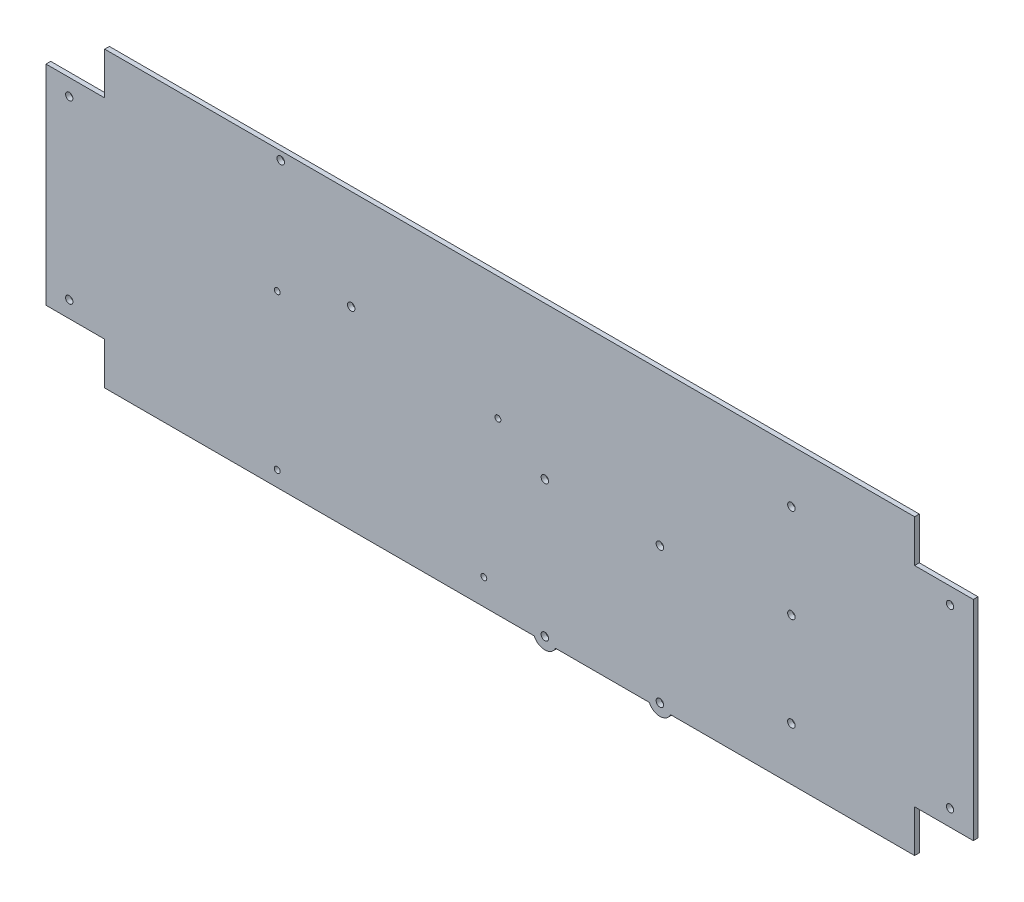
SolidWorks part; units mm, degrees
material "2014 Alloy"
ref_plane "Plan de face" through (0, 0, 0) normal (0, 0, 1) x (1, 0, 0)
ref_plane "Plan de dessus" through (0, 0, 0) normal (0, 1, 0) x (1, 0, 0)
ref_plane "Plan de droite" through (0, 0, 0) normal (1, 0, 0) x (0, 0, -1)
sketch "Sketch1" plane through (0, 0, 0) normal (0, 0, 1) x (1, 0, 0)
  line L1 (-197.5, 62.5) -> (197.5, 62.5)
  line L2 (-197.5, 62.5) -> (-197.5, -62.5)
  line L3 (-197.5, -62.5) -> (197.5, -62.5)
  line L4 (197.5, 62.5) -> (197.5, -62.5)
  line L5 (-197.5, 62.5) -> (197.5, -62.5) construction
  line L6 (-197.5, -62.5) -> (197.5, 62.5) construction
  point P0 (0, 0)
  dimension "D1" = 125
  dimension "D2" = 395
extrude "Boss-Extrude1" add sketch "Sketch1" along normal blind 2
sketch "Sketch2" plane through (0, 0, 2) normal (0, 0, 1) x (1, 0, 0)
  line L1 (-187.6, 37.5) -> (187.6, 37.5) construction
  line L2 (-187.6, 37.5) -> (-187.6, -37.5) construction
  line L3 (-187.6, -37.5) -> (187.6, -37.5) construction
  line L4 (187.6, 37.5) -> (187.6, -37.5) construction
  line L5 (-187.6, 37.5) -> (187.6, -37.5) construction
  line L6 (-187.6, -37.5) -> (187.6, 37.5) construction
  circle A0 centre (-187.6, 37.5) radius 1.55
  circle A1 centre (-187.6, -37.5) radius 1.55
  circle A2 centre (187.6, 37.5) radius 1.55
  circle A3 centre (187.6, -37.5) radius 1.55
  point P0 (0, 0)
  dimension "D1" = 75
  dimension "D2" = 375.2
extrude "Fixing_holes" cut sketch "Sketch2" against normal through all
sketch "Sketch3" plane through (0, 0, 2) normal (0, 0, 1) x (1, 0, 0)
  line L1 (-197.5, 62.5) -> (-172.5, 62.5)
  line L2 (-197.5, 62.5) -> (-197.5, 44.5)
  line L3 (-197.5, 44.5) -> (-172.5, 44.5)
  line L4 (-172.5, 62.5) -> (-172.5, 44.5)
  dimension "D1" = 18
  dimension "D2" = 25
extrude "Cut-Extrude2" cut sketch "Sketch3" against normal through all
mirror "Mirror1" about plane through (0, 0, 0) normal (0, 1, 0) of "Cut-Extrude2"
mirror "Mirror2" about plane through (0, 0, 0) normal (1, 0, 0) of "Mirror1", "Cut-Extrude2"
sketch "Sketch4" plane through (0, 0, 2) normal (0, 0, 1) x (1, 0, 0)
  line L0 (-99, 10) -> (-5, 10) construction
  line L1 (-99, 10) -> (-99, -56) construction
  circle A0 centre (-99, 10) radius 1.25
  circle A1 centre (-99, -56) radius 1.25
  circle A2 centre (-5, 10) radius 1.25
  circle A3 centre (-11, -51.5) radius 1.25
  dimension "D4" = 66
  dimension "D5" = 94
  dimension "D7" = 61.5
  dimension "D8" = 6
  dimension "D1" = 5
  dimension "D2" = 10
extrude "Cave_board_holes" cut sketch "Sketch4" against normal through all
sketch "Sketch5" plane through (0, 0, 2) normal (0, 0, 1) x (1, 0, 0)
  line L1 (15, -2.4) -> (64, -2.4) construction
  line L2 (15, -2.4) -> (15, -60.4) construction
  line L3 (15, -60.4) -> (64, -60.4) construction
  line L4 (64, -2.4) -> (64, -60.4) construction
  circle A0 centre (15, -2.4) radius 1.6
  circle A1 centre (15, -60.4) radius 1.6
  circle A2 centre (64, -2.4) radius 1.6
  circle A3 centre (64, -60.4) radius 1.6
  dimension "D1" = 58
  dimension "D2" = 49
  dimension "D3" = 15
  dimension "D4" = 2.4
extrude "RPi_holes" cut sketch "Sketch5" against normal through all
sketch "Sketch6" plane through (0, 0, 2) normal (0, 0, 1) x (1, 0, 0)
  line L1 (-97.5, 59) -> (-67.5, 59) construction
  line L2 (-97.5, 59) -> (-97.5, 20) construction
  line L3 (-97.5, 20) -> (-67.5, 20) construction
  line L4 (-67.5, 59) -> (-67.5, 20) construction
  circle A0 centre (-97.5, 59) radius 1.6
  circle A3 centre (-67.5, 20) radius 1.6
  dimension "D1" = 39
  dimension "D2" = 30
  dimension "D3" = 67.5
  dimension "D4" = 20
extrude "buzzer_holes" cut sketch "Sketch6" against normal through all
sketch "Sketch7" plane through (0, 0, 2) normal (0, 0, 1) x (1, 0, 0)
  line L0 (0, 0) -> (178.5314, 0) construction
  circle A0 centre (120, 0) radius 1.6
  circle A1 centre (120, 40) radius 1.6
  circle A2 centre (120, -40) radius 1.6
  dimension "D4" = 120
  dimension "D5" = 40
extrude "relays_holes" cut sketch "Sketch7" against normal through all
sketch "Sketch8" plane through (0, 0, 2) normal (0, 0, 1) x (1, 0, 0)
  line L0 (-172.5, -62.5) -> (172.5, -62.5) construction
  line L2 (10.4624, -62.5) -> (19.5376, -62.5)
  line L3 (59.4624, -62.5) -> (68.5376, -62.5)
  arc A0 (10.4624, -62.5) -> (19.5376, -62.5) centre (15, -60.4) ccw
  arc A1 (59.4624, -62.5) -> (68.5376, -62.5) centre (64, -60.4) ccw
  dimension "D1" = 10
  dimension "D2" = 10
extrude "Boss-Extrude2" add sketch "Sketch8" against normal up to surface (2 mm away) up to face at (121.6, -40, 0)
